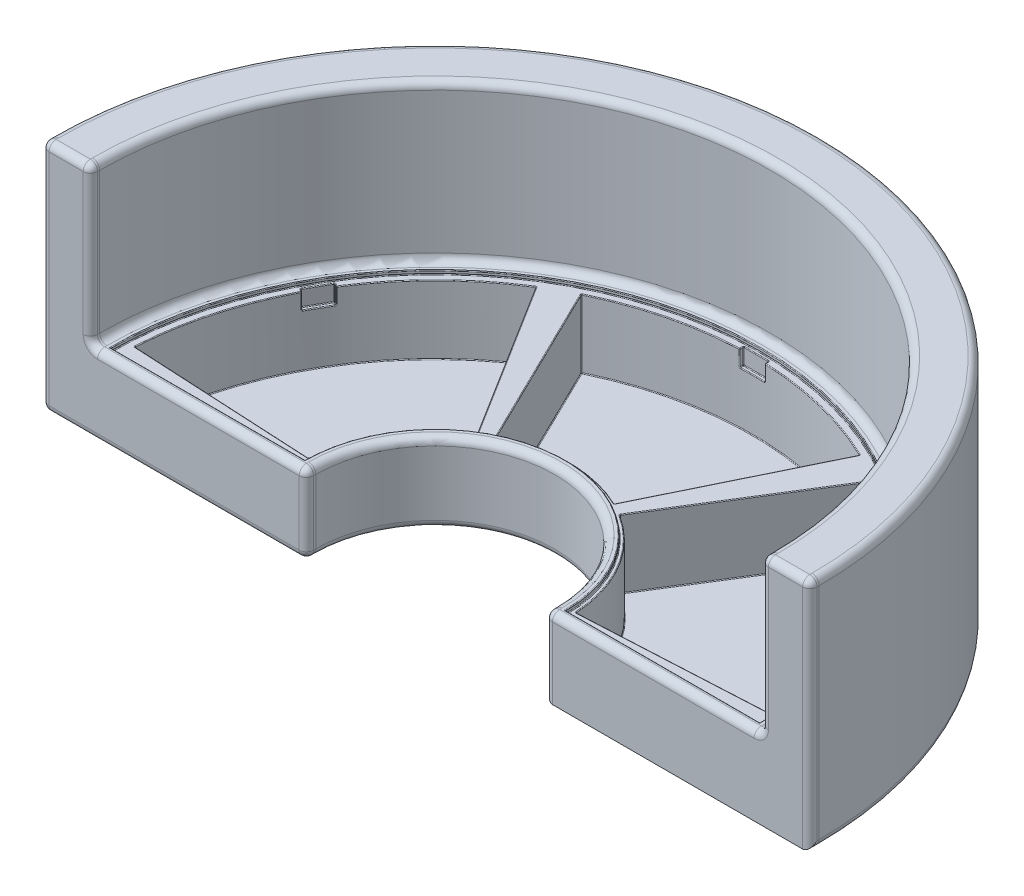
SolidWorks part; units mm, degrees
ref_plane "Front Plane" through (0, 0, 0) normal (0, 0, 1) x (1, 0, 0)
ref_plane "Top Plane" through (0, 0, 0) normal (0, 1, 0) x (1, 0, 0)
ref_plane "Right Plane" through (0, 0, 0) normal (1, 0, 0) x (0, 0, -1)
sketch "Sketch1" plane through (0, 0, 0) normal (0, 1, 0) x (1, 0, 0)
  line L0 (-1066.6, 0) -> (-331.6, 0)
  line L1 (331.6, 0) -> (1066.6, 0)
  arc A0 (1066.6, 0) -> (-1066.6, 0) centre (0, 0) ccw
  arc A1 (331.6, 0) -> (-331.6, 0) centre (0, 0) ccw
  dimension "D1" = 2133.2
  dimension "D2" = 663.2
extrude "Boss-Extrude1" add sketch "Sketch1" along normal blind 650.4
sketch "Sketch4" plane through (0, 0, 0) normal (0, 0, 1) x (1, 0, 0)
  line L0 (-931.6, 650.4) -> (-931.6, 218.8)
  line L1 (-1066.6, 650.4) -> (-331.6, 650.4) construction
  line L2 (-931.6, 218.8) -> (-331.6, 218.8)
  line L3 (-331.6, 650.4) -> (-331.6, 0) construction
  line L4 (-1066.6, 650.4) -> (-1066.6, 0) construction
  line L5 (-1066.6, 0) -> (-331.6, 0) construction
  line L6 (-931.6, 650.4) -> (-331.6, 650.4)
  line L7 (-331.6, 650.4) -> (-331.6, 218.8)
  dimension "D1" = 135
  dimension "D2" = 218.8
revolve "Cut-Revolve1" cut sketch "Sketch4" angle 180 about axis through (0, 650.4, 0) along (0, -1, 0)
sketch "Sketch11" plane through (0, 0, 0) normal (0, 0, 1) x (1, 0, 0)
  line L0 (-1066.6, 0) -> (-331.6, 0)
  line L1 (-331.6, 0) -> (-331.6, 218.8)
  line L2 (-331.6, 218.8) -> (-931.6, 218.8)
  line L3 (-931.6, 218.8) -> (-931.6, 650.4)
  line L4 (-931.6, 650.4) -> (-1066.6, 650.4)
  line L5 (-1066.6, 650.4) -> (-1066.6, 0)
extrude "Boss-Extrude2" add sketch "Sketch11" along normal blind 26
mirror "Mirror1" about plane through (0, 0, 0) normal (1, 0, 0) of "Boss-Extrude2"
fillet "Fillet1" radius 20 29 edges at (0, 0, -1066.6) (0, 650.4, -1066.6) (0, 650.4, -931.6) (0, 218.8, -931.6) (0, 218.8, -331.6) (0, 0, -331.6) (1066.6, 650.4, 13) (1066.6, 0, 13) (-1066.6, 0, 13) (-331.6, 0, 13) (331.6, 0, 13) (331.6, 218.8, 13) (-1066.6, 650.4, 13) (931.6, 650.4, 13) (-931.6, 650.4, 13) (931.6, 218.8, 13) (-931.6, 218.8, 13) (-331.6, 218.8, 13) (631.6, 218.8, 26) (-631.6, 218.8, 26) (999.1, 650.4, 26) (931.6, 434.6, 26) (1066.6, 325.2, 26) (331.6, 109.4, 26) (-331.6, 109.4, 26) (-699.1, 0, 26) (-931.6, 434.6, 26) (-1066.6, 325.2, 26) (-999.1, 650.4, 26)
sketch "Sketch5" plane through (0, 218.8, 0) normal (0, 1, 0) x (1, 0, 0)
  line L2 (-880.3918, 46.1394) -> (-371.0907, 19.448)
  line L3 (371.0907, 19.448) -> (880.3918, 46.1394)
  line L4 (0, 0) -> (-880.3918, 46.1394) construction
  line L6 (0, 0) -> (914.52, 47.928) construction
  line L8 (0, 0) -> (-427.4082, 771.0647) construction
  line L9 (0, 0) -> (427.4082, 771.0647) construction
  line L10 (0, 0) -> (-467.1768, 747.6392) construction
  line L11 (0, 0) -> (-386.468, 792.3768) construction
  line L12 (0, 0) -> (386.468, 792.3768) construction
  line L13 (0, 0) -> (467.1768, 747.6392) construction
  line L14 (-196.918, 315.1347) -> (-467.1768, 747.6392)
  line L15 (-911.6, -6) -> (-351.6, -6) construction
  line L16 (-162.8987, 333.9919) -> (-386.468, 792.3768)
  line L17 (351.6, -6) -> (911.6, -6) construction
  line L18 (162.8987, 333.9919) -> (386.468, 792.3768)
  line L20 (196.918, 315.1347) -> (467.1768, 747.6392)
  arc A0 (-371.0907, 19.448) -> (-196.918, 315.1347) centre (0, 0) cw
  arc A1 (-880.3918, 46.1394) -> (-467.1768, 747.6392) centre (0, 0) cw
  arc A2 (911.6, 0) -> (-911.6, 0) centre (0, 0) ccw construction
  arc A3 (351.6, 0) -> (-351.6, 0) centre (0, 0) ccw construction
  arc A4 (-162.8987, 333.9919) -> (162.8987, 333.9919) centre (0, 0) cw
  arc A5 (-386.468, 792.3768) -> (386.468, 792.3768) centre (0, 0) cw
  arc A6 (467.1768, 747.6392) -> (880.3918, 46.1394) centre (0, 0) cw
  arc A7 (196.918, 315.1347) -> (371.0907, 19.448) centre (0, 0) cw
  dimension "D1" = 30
  dimension "D2" = 20
  dimension "D3" = 177
  dimension "D4" = 3
  dimension "D5" = 58
  dimension "D6" = 58
  dimension "D7" = 3
  dimension "D8" = 3
  dimension "D11" = 3
  dimension "D12" = 3
  dimension "D13" = 3
extrude "Cut-Extrude1" cut sketch "Sketch5" against normal blind 200
sketch "Sketch6" plane through (0, 218.8, 0) normal (0, 1, 0) x (1, 0, 0)
  line L12 (-901.6, 0) -> (-361.6, 0)
  line L13 (361.6, 0) -> (901.6, 0)
  arc A6 (-361.6, 0) -> (361.6, 0) centre (0, 0) cw
  arc A9 (-901.6, 0) -> (901.6, 0) centre (0, 0) cw
  arc A10 (-467.1768, 747.6392) -> (-880.3918, 46.1394) centre (0, 0) ccw construction
  arc A11 (-196.918, 315.1347) -> (-371.0907, 19.448) centre (0, 0) ccw construction
  point P2 (0, 0)
  point P3 (0, 0)
  dimension "D1" = 20
  dimension "D2" = 10
extrude "Cut-Extrude2" cut sketch "Sketch6" against normal blind 10
sketch "Sketch10" plane through (0, 208.8, 0) normal (0, 1, 0) x (1, 0, 0)
  line L0 (-780.988, 410.4891) -> (-745.988, 471.1109) construction
  line L5 (-745.988, 471.1109) -> (-737.3277, 466.1109)
  line L6 (-737.3277, 466.1109) -> (-772.3277, 405.4891)
  line L7 (-772.3277, 405.4891) -> (-780.988, 410.4891)
  line L8 (-780.988, 410.4891) -> (-789.6483, 415.4891)
  line L9 (-911.6, -6) -> (-351.6, -6) construction
  line L10 (-763.488, 440.8) -> (0, 0) construction
  line L11 (-789.6483, 415.4891) -> (-754.6483, 476.1109)
  line L12 (-754.6483, 476.1109) -> (-745.988, 471.1109)
  line L14 (0, 0) -> (-465.8882, 840.4846) construction
  line L15 (0, 0) -> (-467.1768, 747.6392) construction
  arc A2 (-467.1768, 747.6392) -> (-880.3918, 46.1394) centre (0, 0) ccw construction
  dimension "D1" = 70
  dimension "D2" = 10
  dimension "D3" = 10
  dimension "D4" = 3
  dimension "D5" = 30
extrude "Cut-Extrude4" cut sketch "Sketch10" against normal blind 45
pattern_circular "CirPattern2" count 3 over 120 about axis through (0, 0, 0) along (0, 1, 0) of "Cut-Extrude4"
fillet "Fillet2" radius 2 77 edges at (-759.6123, 18.8, -447.4458) (-320.1814, 18.8, -188.6013) (-763.488, 163.8, -440.8) (-745.3861, 186.3, -470.7634) (-780.3861, 186.3, -410.1416) (0, 218.8, -901.6) (0, 218.8, -361.6) (-320.1814, 208.8, -188.6013) (-371.0907, 113.8, -19.448) (-631.6, 208.8, 0) (-880.3918, 113.8, -46.1394) (-850.1001, 208.8, -233.5559) (-621.886, 208.8, -624.881) (-467.1768, 113.8, -747.6392) (-332.0474, 208.8, -531.3869) (-196.918, 113.8, -315.1347) (-625.7413, 18.8, -32.7937) (-332.0474, 18.8, -531.3869) (0, 208.8, -371.6) (-162.8987, 113.8, -333.9919) (-274.6834, 208.8, -563.1843) (-386.468, 113.8, -792.3768) (-215.3326, 208.8, -854.8979) (-35, 186.3, -880.905) (0, 163.8, -881.6) (35, 186.3, -880.905) (215.3326, 208.8, -854.8979) (386.468, 113.8, -792.3768) (274.6834, 208.8, -563.1843) (162.8987, 113.8, -333.9919) (-274.6834, 18.8, -563.1843) (0, 18.8, -881.6) (274.6834, 18.8, -563.1843) (0, 18.8, -371.6) (320.1814, 208.8, -188.6013) (196.918, 113.8, -315.1347) (332.0474, 208.8, -531.3869) (467.1768, 113.8, -747.6392) (621.886, 208.8, -624.881) (745.3861, 186.3, -470.7634) (763.488, 163.8, -440.8) (780.3861, 186.3, -410.1416) (850.1001, 208.8, -233.5559) (880.3918, 113.8, -46.1394) (371.0907, 113.8, -19.448) (332.0474, 18.8, -531.3869) (759.6123, 18.8, -447.4458) (625.7413, 18.8, -32.7937) (320.1814, 18.8, -188.6013) (789.6483, 186.3, -415.4891) (772.1483, 163.8, -445.8) (754.6483, 186.3, -476.1109) (-35, 163.8, -886.2525) (35, 163.8, -886.2525) (35, 186.3, -891.6) (0, 163.8, -891.6) (-35, 186.3, -891.6) (-750.0172, 163.8, -473.4371) (-785.0172, 163.8, -412.8154) (-754.6483, 186.3, -476.1109) (-772.1483, 163.8, -445.8) (-789.6483, 186.3, -415.4891) (750.0172, 208.8, -473.4371) (0, 208.8, -361.6) (-750.0172, 208.8, -473.4371) (-772.1483, 208.8, -445.8) (-785.0172, 208.8, -412.8154) (0, 208.8, -901.6) (785.0172, 208.8, -412.8154) (772.1483, 208.8, -445.8) (-35, 208.8, -886.2525) (35, 208.8, -886.2525) (0, 208.8, -891.6) (625.7413, 208.8, -32.7937) (-625.7413, 208.8, -32.7937) (631.6, 218.8, 0) (-631.6, 218.8, 0)
